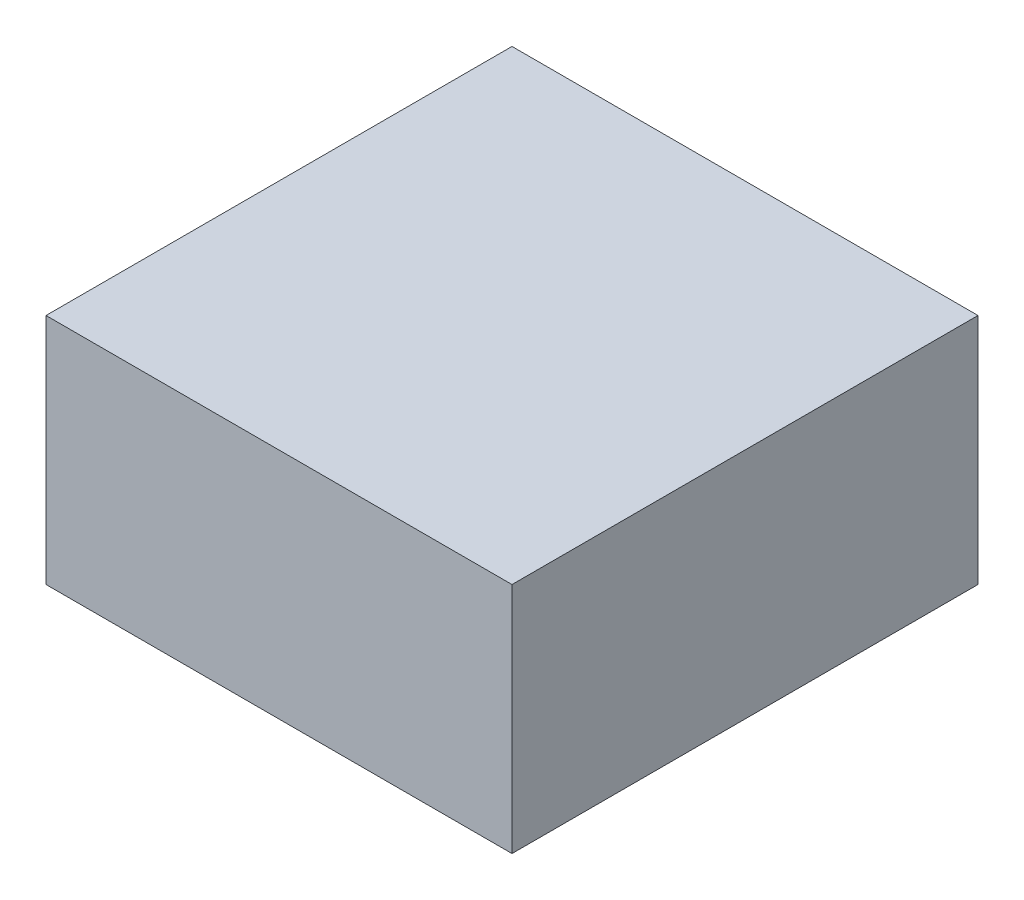
SolidWorks part; units mm, degrees
ref_plane "Front Plane" through (0, 0, 0) normal (0, 0, 1) x (1, 0, 0)
ref_plane "Top Plane" through (0, 0, 0) normal (0, 1, 0) x (1, 0, 0)
ref_plane "Right Plane" through (0, 0, 0) normal (1, 0, 0) x (0, 0, -1)
sketch "Sketch1" plane through (0, 0, 0) normal (0, 1, 0) x (1, 0, 0)
  line L1 (-50, -50) -> (50, -50)
  line L2 (-50, -50) -> (-50, 50)
  line L3 (-50, 50) -> (50, 50)
  line L4 (50, -50) -> (50, 50)
  line L5 (-50, -50) -> (50, 50) construction
  line L6 (-50, 50) -> (50, -50) construction
  point P0 (0, 0)
  dimension "D1" = 100
extrude "Boss-Extrude1" add sketch "Sketch1" along normal blind 50
